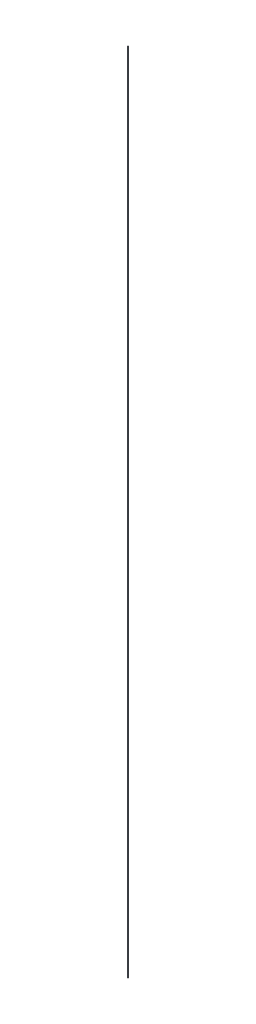
SolidWorks part; units mm, degrees
ref_plane "Front Plane" through (0, 0, 0) normal (0, 0, 1) x (1, 0, 0)
ref_plane "Top Plane" through (0, 0, 0) normal (0, 1, 0) x (1, 0, 0)
ref_plane "Right Plane" through (0, 0, 0) normal (1, 0, 0) x (0, 0, -1)
sketch "Sketch1" plane through (0, 0, 0) normal (0, 1, 0) x (1, 0, 0)
  circle A0 centre (0, 0) radius 1.5
  dimension "D1" = 3
extrude "Boss-Extrude1" add sketch "Sketch1" along normal blind 3000
ref_point "Point2"
ref_point "Point4"
